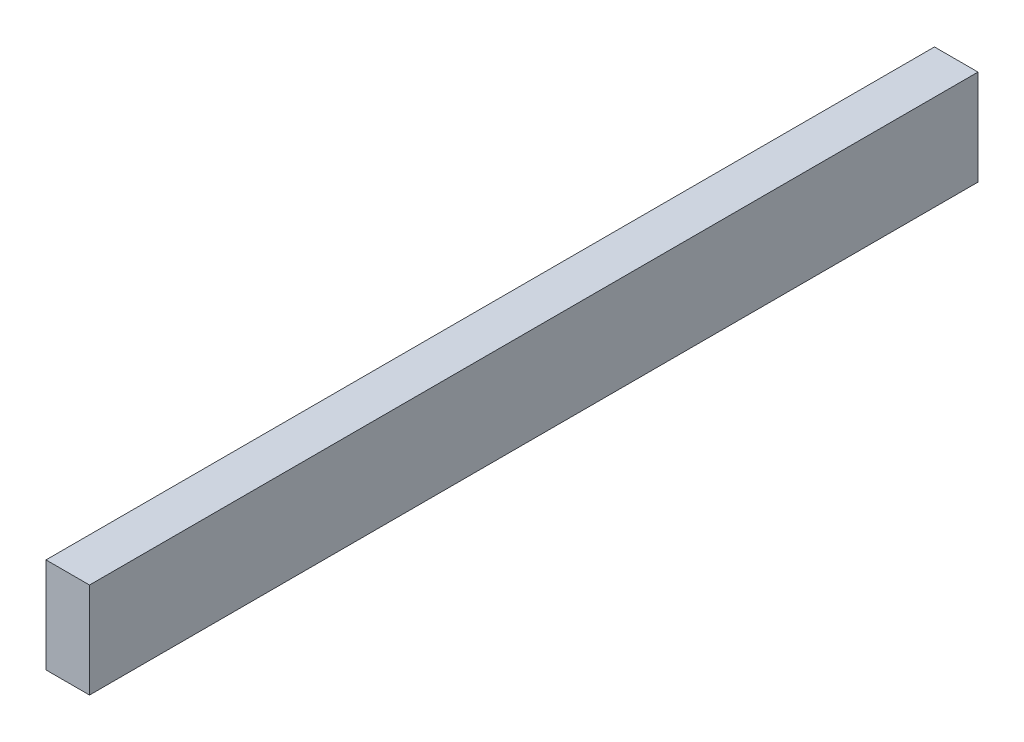
SolidWorks part; units mm, degrees
ref_plane "Front Plane" through (0, 0, 0) normal (0, 0, 1) x (1, 0, 0)
ref_plane "Top Plane" through (0, 0, 0) normal (0, 1, 0) x (1, 0, 0)
ref_plane "Right Plane" through (0, 0, 0) normal (1, 0, 0) x (0, 0, -1)
sketch "Sketch1" plane through (0, 0, 0) normal (0, 0, 1) x (1, 0, 0)
  line L1 (-3.429, -7.51) -> (3.429, -7.51)
  line L2 (-3.429, -7.51) -> (-3.429, 7.51)
  line L3 (-3.429, 7.51) -> (3.429, 7.51)
  line L4 (3.429, -7.51) -> (3.429, 7.51)
  line L5 (-3.429, -7.51) -> (3.429, 7.51) construction
  line L6 (-3.429, 7.51) -> (3.429, -7.51) construction
  point P0 (0, 0)
  dimension "D1" = 15.02
  dimension "D2" = 6.858
extrude "Boss-Extrude1" add sketch "Sketch1" along normal mid plane 140
